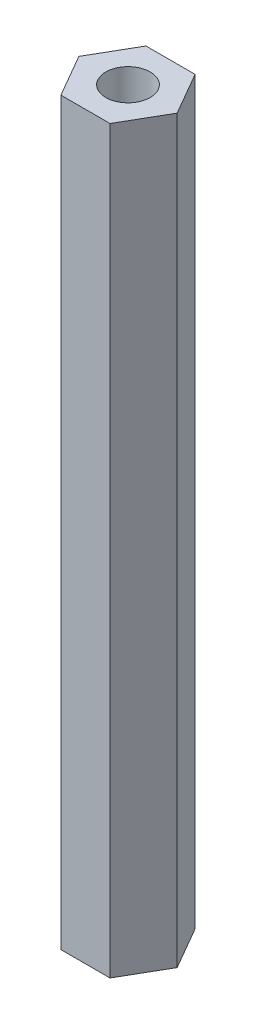
SolidWorks part; units mm, degrees
other "Markup1"
sketch "Sketch2" plane through (2.6558, 40, 2.3) normal (0.3825, 0.9065, 0.1787) x (0.7461, -0.1889, -0.6385)
ref_plane "Front Plane" through (0, 0, 0) normal (0, 0, 1) x (1, 0, 0)
ref_plane "Top Plane" through (0, 0, 0) normal (0, 1, 0) x (1, 0, 0)
ref_plane "Right Plane" through (0, 0, 0) normal (1, 0, 0) x (0, 0, -1)
sketch "Sketch1" plane through (0, 0, 0) normal (0, 1, 0) x (1, 0, 0)
  line L1 (2.6558, 0) -> (1.3279, 2.3)
  line L2 (1.3279, 2.3) -> (-1.3279, 2.3)
  line L3 (-1.3279, 2.3) -> (-2.6558, 0)
  line L4 (-2.6558, 0) -> (-1.3279, -2.3)
  line L5 (-1.3279, -2.3) -> (1.3279, -2.3)
  line L6 (1.3279, -2.3) -> (2.6558, 0)
  circle A0 centre (0, 0) radius 2.3 construction
  circle A2 centre (0, 0) radius 1.2
  dimension "D2" = 1.2
  dimension "D1" = 4.6
extrude "Boss-Extrude1" add sketch "Sketch1" along normal blind 40
